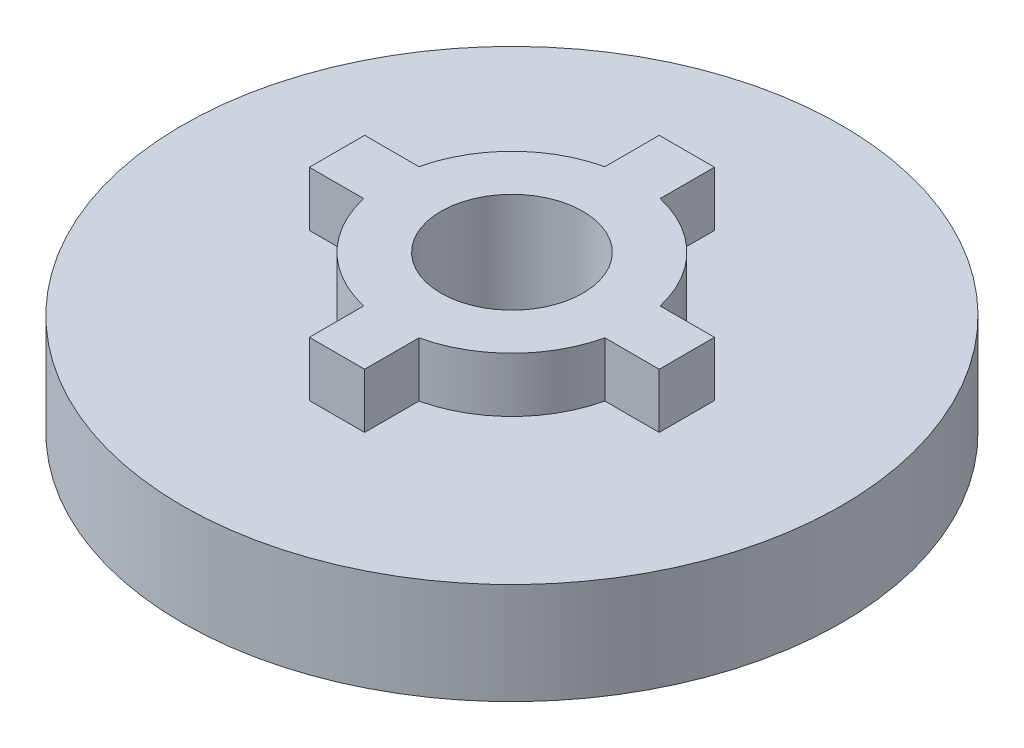
SolidWorks part; units mm, degrees
ref_plane "Front Plane" through (0, 0, 0) normal (0, 0, 1) x (1, 0, 0)
ref_plane "Top Plane" through (0, 0, 0) normal (0, 1, 0) x (1, 0, 0)
ref_plane "Right Plane" through (0, 0, 0) normal (1, 0, 0) x (0, 0, -1)
sketch "Sketch1" plane through (0, 0, 0) normal (0, 1, 0) x (1, 0, 0)
  circle A0 centre (0, 0) radius 32.5
extrude "Boss-Extrude1" add sketch "Sketch1" along normal blind 10
sketch "Sketch2" plane through (0, 10, 0) normal (0, 1, 0) x (1, 0, 0)
  line L0 (2.725, 11.8918) -> (2.725, 17.25)
  line L1 (-17.25, 2.725) -> (-11.8918, 2.725)
  line L2 (-17.25, 2.725) -> (-17.25, -2.725)
  line L3 (-17.25, -2.725) -> (-11.8918, -2.725)
  line L4 (17.25, 2.725) -> (17.25, -2.725)
  line L5 (-2.725, 11.8918) -> (-2.725, 17.25)
  line L6 (11.8918, -2.725) -> (17.25, -2.725)
  line L7 (-2.725, -17.25) -> (2.725, -17.25)
  line L8 (-2.725, -17.25) -> (-2.725, -11.8918)
  line L9 (-2.725, 17.25) -> (2.725, 17.25)
  line L10 (2.725, -17.25) -> (2.725, -11.8918)
  line L11 (11.8918, 2.725) -> (17.25, 2.725)
  arc A0 (11.8918, 2.725) -> (2.725, 11.8918) centre (0, 0) ccw
  arc A1 (-11.8918, -2.725) -> (-2.725, -11.8918) centre (0, 0) ccw
  arc A2 (-2.725, 11.8918) -> (-11.8918, 2.725) centre (0, 0) ccw
  arc A3 (2.725, -11.8918) -> (11.8918, -2.725) centre (0, 0) ccw
  dimension "D1" = 34.5
  dimension "D2" = 5.45
  dimension "D3" = 34.5
  dimension "D4" = 5.45
extrude "Boss-Extrude2" add sketch "Sketch2" along normal blind 5.4
sketch "Sketch3" plane through (0, 15.4, 0) normal (0, 1, 0) x (1, 0, 0)
  circle A0 centre (0, 0) radius 7
extrude "Cut-Extrude1" cut sketch "Sketch3" against normal through all
